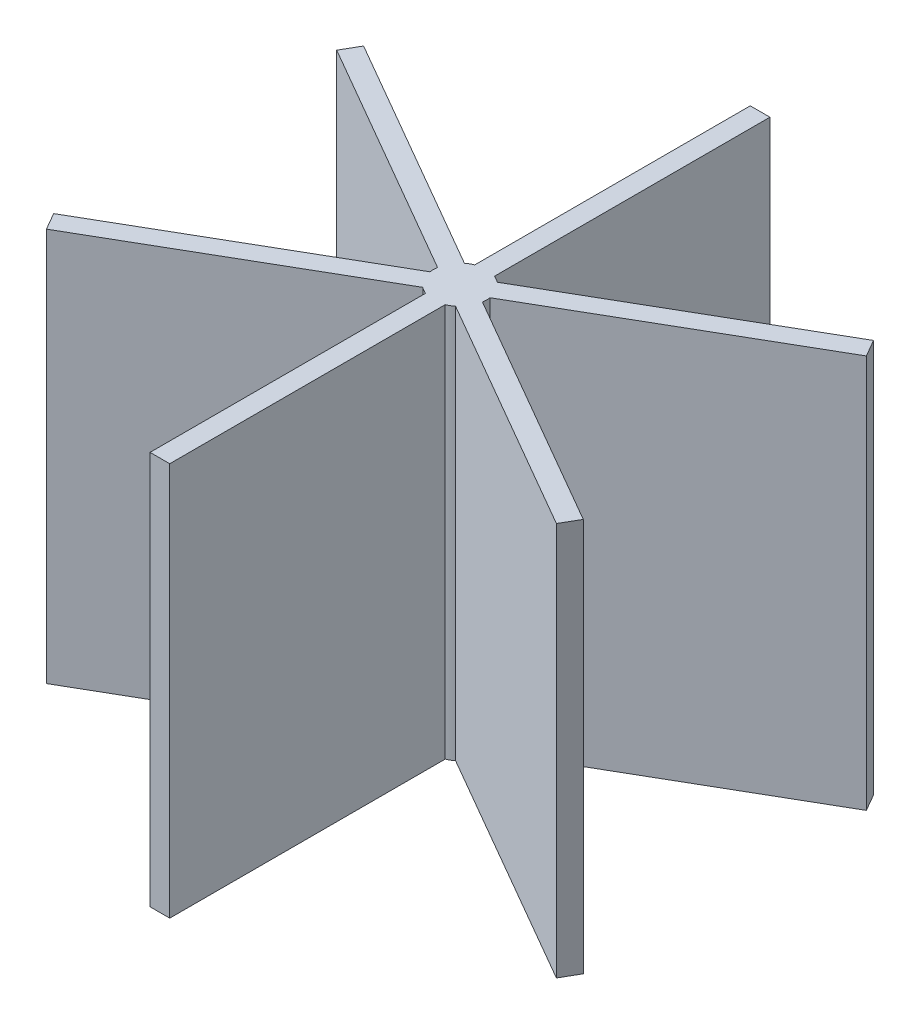
SolidWorks part; units mm, degrees
ref_plane "Front Plane" through (0, 0, 0) normal (0, 0, 1) x (1, 0, 0)
ref_plane "Top Plane" through (0, 0, 0) normal (0, 1, 0) x (1, 0, 0)
ref_plane "Right Plane" through (0, 0, 0) normal (1, 0, 0) x (0, 0, -1)
sketch "Sketch1" plane through (0, 0, 0) normal (0, 1, 0) x (1, 0, 0)
  line L2 (-1.27, 3.175) -> (-1.27, 38.735)
  line L3 (-1.27, 38.735) -> (1.27, 38.735)
  line L4 (1.27, 3.175) -> (1.27, 38.735)
  line L5 (2.1146, 2.6874) -> (32.9105, 20.4674)
  line L6 (32.9105, 20.4674) -> (34.1805, 18.2676)
  line L7 (3.3846, 0.4876) -> (34.1805, 18.2676)
  line L9 (3.3846, -0.4876) -> (34.1805, -18.2676)
  line L10 (34.1805, -18.2676) -> (32.9105, -20.4674)
  line L11 (2.1146, -2.6874) -> (32.9105, -20.4674)
  line L13 (1.27, -3.175) -> (1.27, -38.735)
  line L14 (1.27, -38.735) -> (-1.27, -38.735)
  line L15 (-1.27, -3.175) -> (-1.27, -38.735)
  line L17 (-2.1146, -2.6874) -> (-32.9105, -20.4674)
  line L18 (-32.9105, -20.4674) -> (-34.1805, -18.2676)
  line L19 (-3.3846, -0.4876) -> (-34.1805, -18.2676)
  line L21 (-3.3846, 0.4876) -> (-34.1805, 18.2676)
  line L22 (-34.1805, 18.2676) -> (-32.9105, 20.4674)
  line L23 (-2.1146, 2.6874) -> (-32.9105, 20.4674)
  arc A0 (-3.3846, 0.4876) -> (-3.3846, -0.4876) centre (0, 0) ccw
  arc A1 (-1.27, 3.175) -> (-2.1146, 2.6874) centre (0, 0) ccw
  arc A2 (2.1146, 2.6874) -> (1.27, 3.175) centre (0, 0) ccw
  arc A3 (3.3846, -0.4876) -> (3.3846, 0.4876) centre (0, 0) ccw
  arc A4 (1.27, -3.175) -> (2.1146, -2.6874) centre (0, 0) ccw
  arc A5 (-2.1146, -2.6874) -> (-1.27, -3.175) centre (0, 0) ccw
  point P4 (0, 38.735)
  point P28 (0, 0)
  point P29 (0, -38.735)
  dimension "D1" = 2.54
  dimension "D2" = 35.56
  dimension "D3" = 3.175
  dimension "D4" = 6
extrude "Boss-Extrude1" add sketch "Sketch1" along normal blind 50.8
